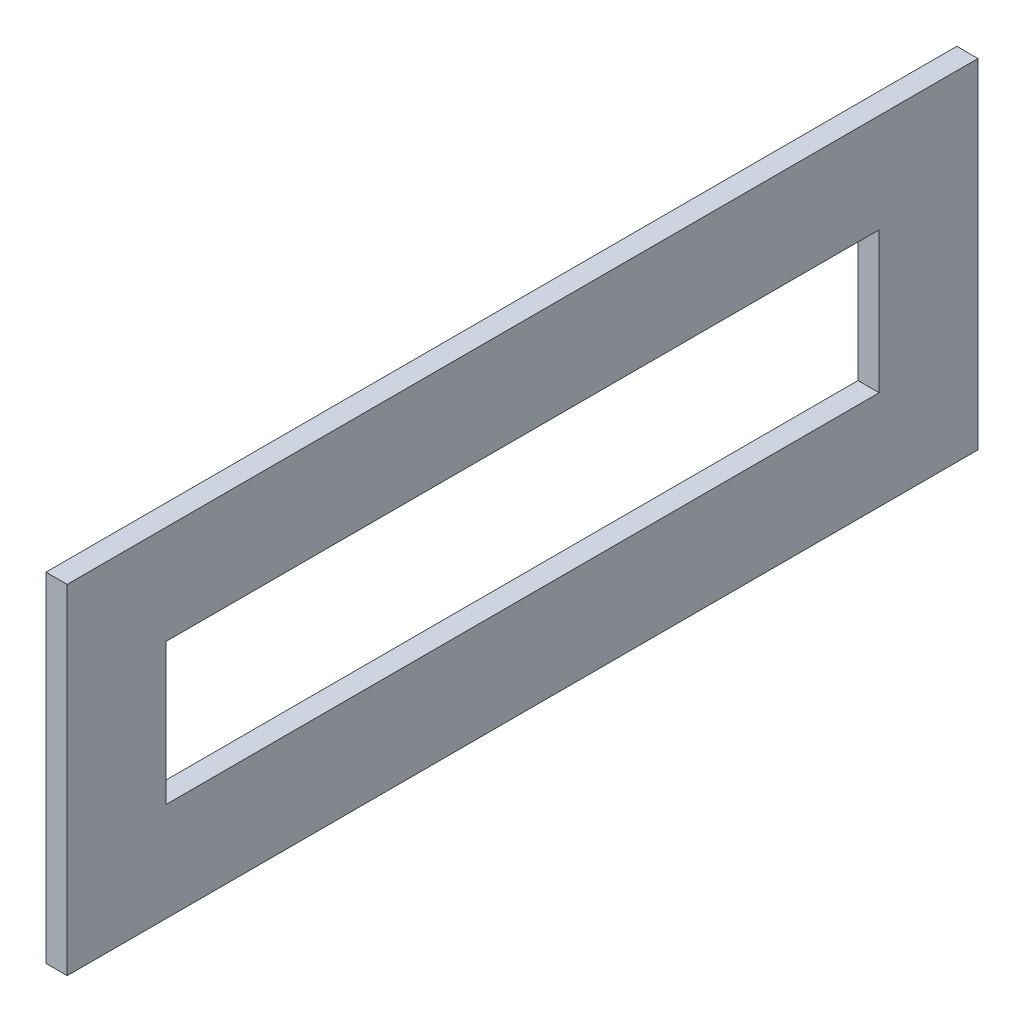
SolidWorks part; units mm, degrees
ref_plane "Front Plane" through (0, 0, 0) normal (0, 0, 1) x (1, 0, 0)
ref_plane "Top Plane" through (0, 0, 0) normal (0, 1, 0) x (1, 0, 0)
ref_plane "Right Plane" through (0, 0, 0) normal (1, 0, 0) x (0, 0, -1)
sketch "Sketch1" plane through (0, 0, 0) normal (1, 0, 0) x (0, 0, -1)
  line L1 (-64.5, 75.1235) -> (64.5, 75.1235)
  line L2 (-64.5, 75.1235) -> (-64.5, 27.1235)
  line L3 (-64.5, 27.1235) -> (64.5, 27.1235)
  line L4 (64.5, 75.1235) -> (64.5, 27.1235)
  line L5 (-64.5, 75.1235) -> (64.5, 27.1235) construction
  line L6 (-64.5, 27.1235) -> (64.5, 75.1235) construction
  line L7 (-50.5, 61.1235) -> (50.5, 61.1235)
  line L8 (-50.5, 61.1235) -> (-50.5, 41.1235)
  line L9 (-50.5, 41.1235) -> (50.5, 41.1235)
  line L10 (50.5, 61.1235) -> (50.5, 41.1235)
  line L11 (-50.5, 61.1235) -> (50.5, 41.1235) construction
  line L12 (-50.5, 41.1235) -> (50.5, 61.1235) construction
  point P0 (0, 51.1235)
  point P5 (0, 51.1235)
  dimension "D1" = 129
  dimension "D2" = 48
  dimension "D3" = 20
  dimension "D4" = 101
extrude "Boss-Extrude1" add sketch "Sketch1" along normal blind 3
